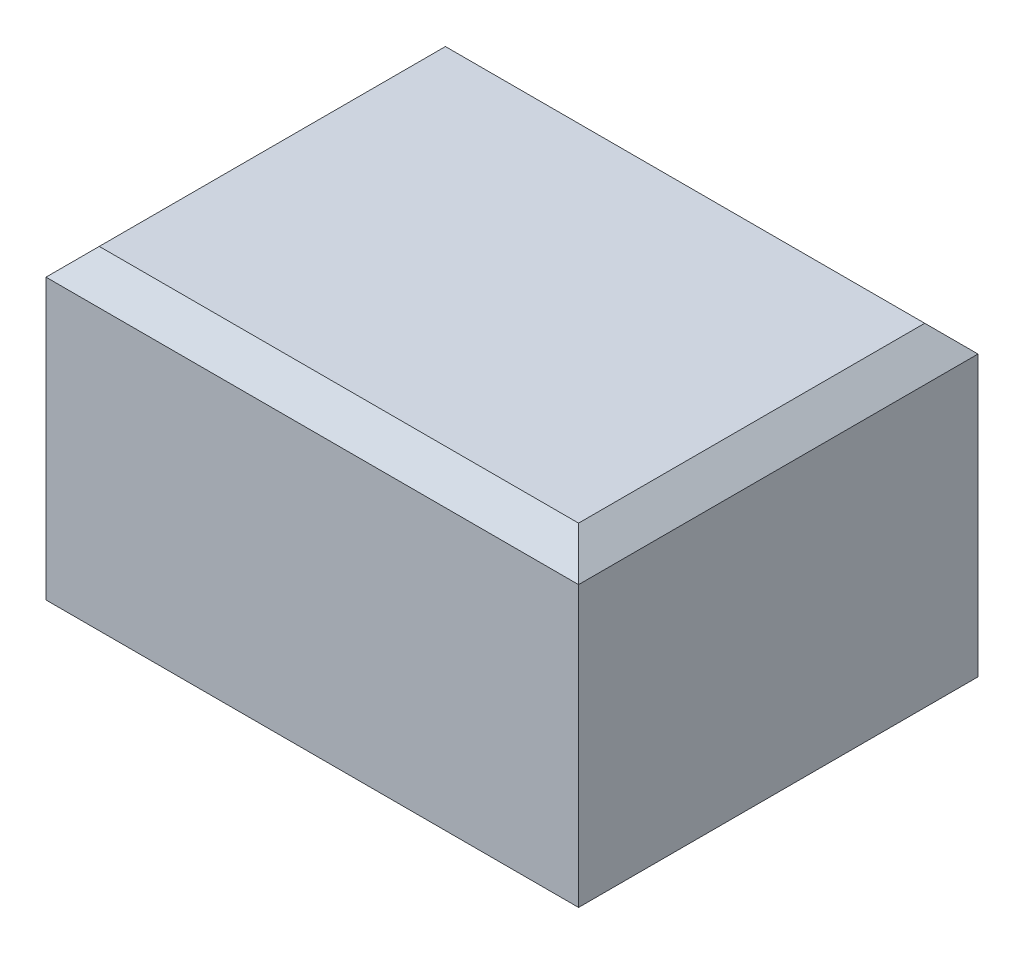
SolidWorks part; units mm, degrees
ref_plane "Front Plane" through (0, 0, 0) normal (0, 0, 1) x (1, 0, 0)
ref_plane "Top Plane" through (0, 0, 0) normal (0, 1, 0) x (1, 0, 0)
ref_plane "Right Plane" through (0, 0, 0) normal (1, 0, 0) x (0, 0, -1)
sketch "Sketch1" plane through (0, 0, 0) normal (0, 1, 0) x (1, 0, 0)
  line L1 (-200, 150) -> (200, 150)
  line L2 (-200, 150) -> (-200, -150)
  line L3 (-200, -150) -> (200, -150)
  line L4 (200, 150) -> (200, -150)
  line L5 (-200, 150) -> (200, -150) construction
  line L6 (-200, -150) -> (200, 150) construction
  point P0 (0, 0)
  dimension "D1" = 400
  dimension "D2" = 300
extrude "Boss-Extrude1" add sketch "Sketch1" along normal blind 250
chamfer "Chamfer1" distance 20 angle 45 8 edges at (0, 0, -150) (-200, 0, 0) (0, 0, 150) (200, 0, 0) (0, 250, 150) (-200, 250, 0) (0, 250, -150) (200, 250, 0)
